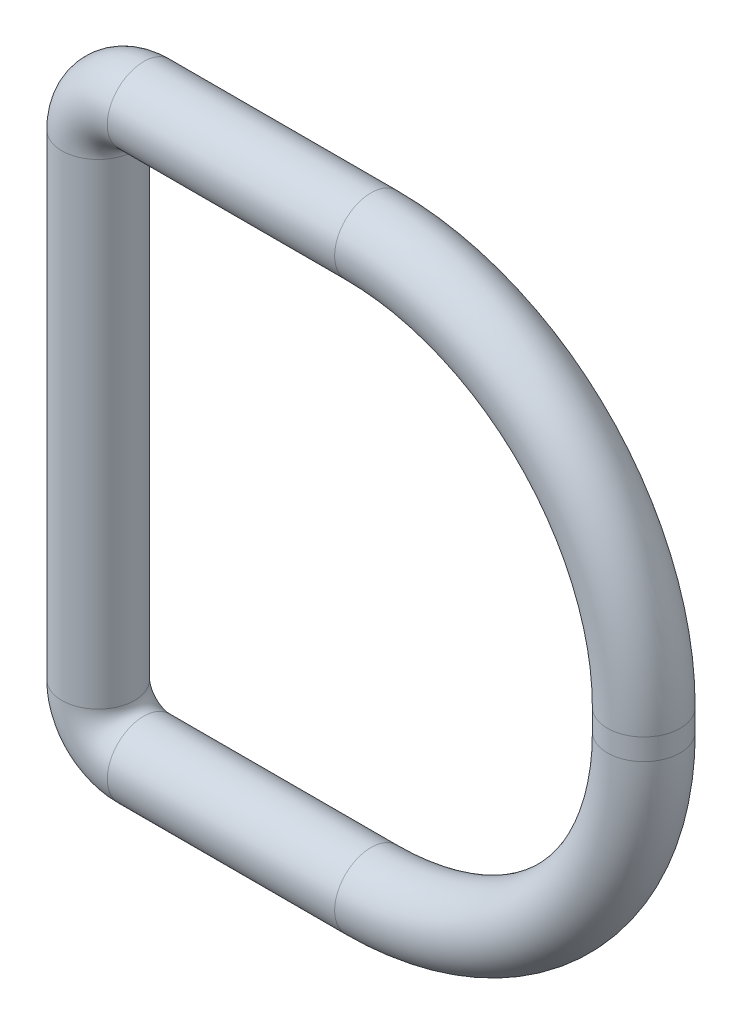
SolidWorks part; units mm, degrees
ref_plane "Plan de face" through (0, 0, 0) normal (0, 0, 1) x (1, 0, 0)
ref_plane "Plan de dessus" through (0, 0, 0) normal (0, 1, 0) x (1, 0, 0)
ref_plane "Plan de droite" through (0, 0, 0) normal (1, 0, 0) x (0, 0, -1)
sketch "Esquisse1" plane through (0, 0, 0) normal (0, 0, 1) x (1, 0, 0)
  line L4 (2.5, 25.6729) -> (2.5, -0.5)
  line L5 (5, 28.1729) -> (17.5, 28.1729)
  line L6 (5, -3) -> (17.5, -3)
  line L7 (32.5, 13.1729) -> (32.5, 12)
  arc A0 (5, 28.1729) -> (2.5, 25.6729) centre (5, 25.6729) ccw
  arc A1 (5, -3) -> (2.5, -0.5) centre (5, -0.5) cw
  arc A2 (17.5, 28.1729) -> (32.5, 13.1729) centre (17.5, 13.1729) cw
  arc A3 (17.5, -3) -> (32.5, 12) centre (17.5, 12) ccw
  dimension "D3" = 2.5
  dimension "D5" = 15
  dimension "D4" = 30
sketch "Esquisse2" plane through (0, 0, 0) normal (0, 1, 0) x (1, 0, 0)
  circle A0 centre (2.5, 0) radius 2
sweep "Balayage2" add profiles "Esquisse2" path "Esquisse1"
